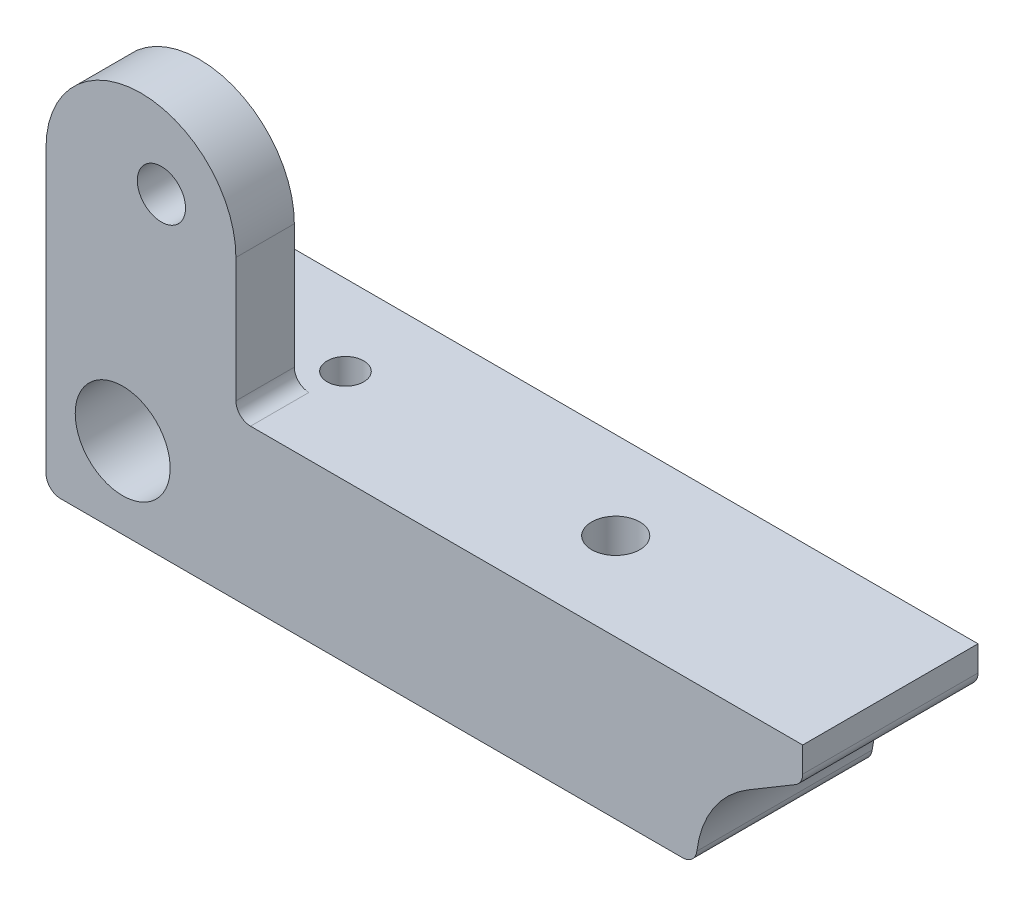
SolidWorks part; units mm, degrees
ref_plane "Front Plane" through (0, 0, 0) normal (0, 0, 1) x (1, 0, 0)
ref_plane "Top Plane" through (0, 0, 0) normal (0, 1, 0) x (1, 0, 0)
ref_plane "Right Plane" through (0, 0, 0) normal (1, 0, 0) x (0, 0, -1)
sketch "Sketch1" plane through (0, 0, 0) normal (0, 0, 1) x (1, 0, 0)
  line L1 (-25.9, 5.4) -> (25.9, 5.4)
  line L2 (-25.9, 5.4) -> (-25.9, -5.4)
  line L3 (-25.9, -5.4) -> (25.9, -5.4)
  line L4 (25.9, 5.4) -> (25.9, -5.4)
  line L5 (-25.9, 5.4) -> (25.9, -5.4) construction
  line L6 (-25.9, -5.4) -> (25.9, 5.4) construction
  point P0 (0, 0)
  dimension "D1" = 51.8
  dimension "D2" = 10.8
extrude "Boss-Extrude1" add sketch "Sketch1" along normal blind 12
sketch "Sketch2" plane through (0, 0, 12) normal (0, 0, 1) x (1, 0, 0)
  line L0 (-25.9, 14.9) -> (-25.9, 5.4)
  line L1 (25.9, 5.4) -> (-25.9, 5.4) construction
  line L2 (-25.9, 5.4) -> (-12.9, 5.4)
  line L3 (-12.9, 5.4) -> (-12.9, 14.9)
  arc A1 (-12.9, 14.9) -> (-25.9, 14.9) centre (-19.4, 14.9) ccw
  dimension "D1" = 6.5
  dimension "D2" = 9.5
extrude "Boss-Extrude2" add sketch "Sketch2" against normal blind 4
sketch "Sketch3" plane through (0, 0, 0) normal (0, 0, -1) x (-1, 0, 0)
  line L1 (25.9, -5.4) -> (-25.9, -5.4) construction
  line L2 (-22.1604, 0.8694) -> (-25.9, 3.1)
  line L3 (-25.9, -5.4) -> (-25.9, 5.4) construction
  line L4 (-25.9, 5.4) -> (25.9, 5.4) construction
  line L5 (-25.9, 3.1) -> (-25.9, -5.4)
  line L6 (-25.9, -5.4) -> (-18.6, -5.4)
  arc A0 (-22.1604, 0.8694) -> (-18.6, -5.4) centre (-25.9, -5.4) cw
  dimension "D1" = 44.5
  dimension "D2" = 2.3
extrude "Cut-Extrude1" cut sketch "Sketch3" against normal through all
fillet "Fillet1" radius 1 5 edges at (18.6, -5.4, 6) (-12.9, 5.4, 10) (-25.9, 5.4, 4) (-25.9, -5.4, 6) (25.9, 3.1, 6)
sketch "Sketch4" plane through (0, 0, 0) normal (0, 0, -1) x (-1, 0, 0)
  line L0 (25.9, 4.4) -> (25.9, -4.4) construction
  line L1 (-25.9, 5.4) -> (24.9, 5.4) construction
  circle A0 centre (20.65, 0.15) radius 3.25
  dimension "D1" = 6.5
  dimension "D2" = 5.25
  dimension "D3" = 5.25
extrude "Cut-Extrude2" cut sketch "Sketch4" against normal through all
sketch "Sketch5" plane through (0, 0, 0) normal (0, 0, -1) x (-1, 0, 0)
  circle A0 centre (20.65, 0.15) radius 4
  dimension "D1" = 8
extrude "Cut-Extrude3" cut sketch "Sketch5" against normal blind 1.05
hole_wizard "M4 Tapped Hole1" positions "Sketch6" profile "Sketch7" tap size "M4" standard "DIN" end condition up to next
sketch "Sketch6" plane through (0, 5.4, 0) normal (0, 1, 0) x (1, 0, 0)
  line L0 (-25.9, -8) -> (-25.9, 0) construction
  line L1 (25.9, 0) -> (-24.9, 0) construction
  point P0 (7.1, -6)
  dimension "D1" = 33
  dimension "D2" = 6
sketch "Sketch7" plane through (7.1, 5.4, 6) normal (1, 0, 0) x (0, 0, 1)
  line L0 (0, 0) -> (0, 10.8)
  line L1 (0, 10.8) -> (1.65, 10.8)
  line L2 (1.65, 10.8) -> (1.65, 0)
  line L5 (1.65, 0) -> (0, 0)
  line L11 (0, -6.35) -> (0, 107.95) construction
  dimension "Thru Tap Drill Dia." = 3.3
  dimension "Thru Tap Drill Depth" = 10.8
cosmetic thread "Hole Thread1" parameters "D2"=4
sketch "Sketch8" plane through (0, 5.4, 0) normal (0, 1, 0) x (1, 0, 0)
  line L0 (-25.9, -8) -> (-25.9, 0) construction
  line L1 (25.9, -12) -> (-11.9, -12) construction
  circle A0 centre (-11.9, -5.5) radius 1.25
  dimension "D3" = 2.5
  dimension "D1" = 14
  dimension "D2" = 6.5
extrude "Cut-Extrude4" cut sketch "Sketch8" against normal through all
hole_wizard "M4 Tapped Hole2" positions "Sketch10" profile "Sketch11" tap size "M4" standard "DIN" end condition up to next
sketch "Sketch10" plane through (0, 0, 12) normal (0, 0, 1) x (1, 0, 0)
  line L0 (-25.9, 14.9) -> (-25.9, -4.4) construction
  line L1 (-24.9, -5.4) -> (17.6605, -5.4) construction
  point P0 (-18, 16.1)
  dimension "D1" = 7.9
  dimension "D2" = 21.5
sketch "Sketch11" plane through (-18, 16.1, 12) normal (1, 0, 0) x (0, -1, 0)
  line L0 (0, 0) -> (0, 4)
  line L1 (0, 4) -> (1.65, 4)
  line L2 (1.65, 4) -> (1.65, 0)
  line L5 (1.65, 0) -> (0, 0)
  line L11 (0, -6.35) -> (0, 107.95) construction
  dimension "Thru Tap Drill Dia." = 3.3
  dimension "Thru Tap Drill Depth" = 4
cosmetic thread "Hole Thread2" parameters "D2"=4
